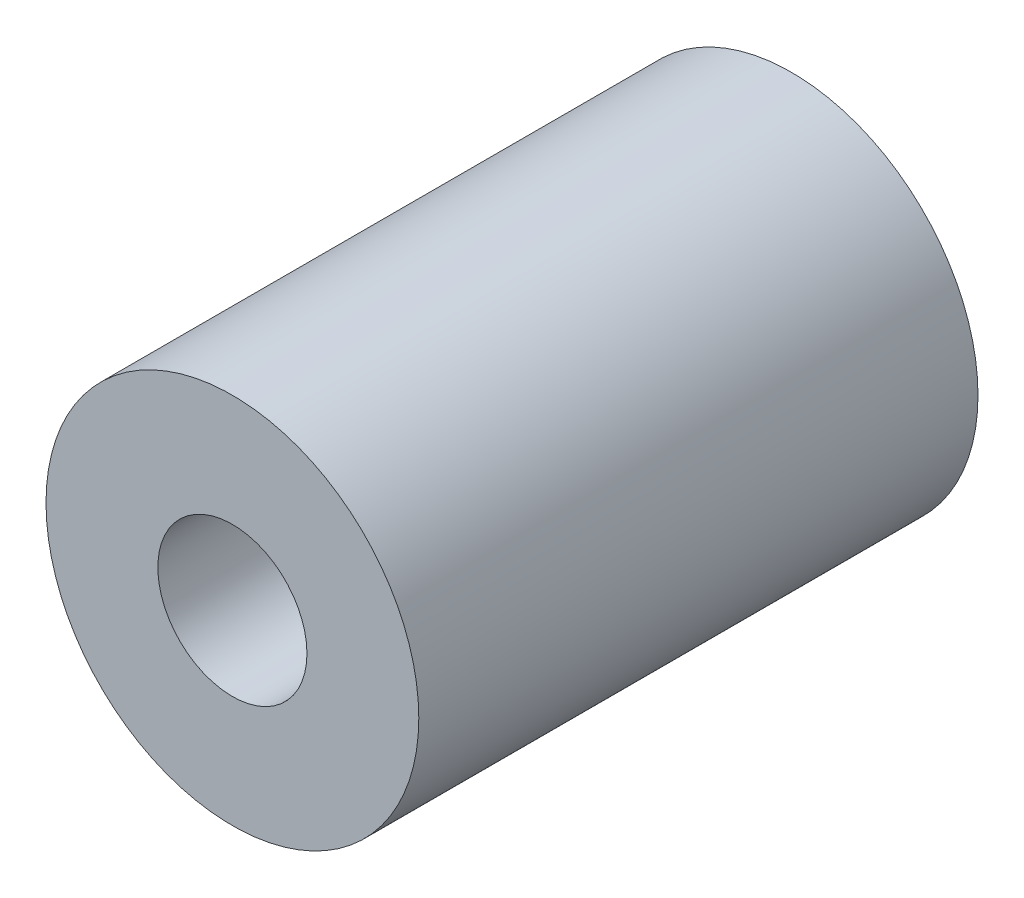
SolidWorks part; units mm, degrees
material "Alloy Steel"
ref_plane "Front Plane" through (0, 0, 0) normal (0, 0, 1) x (1, 0, 0)
ref_plane "Top Plane" through (0, 0, 0) normal (0, 1, 0) x (1, 0, 0)
ref_plane "Right Plane" through (0, 0, 0) normal (1, 0, 0) x (0, 0, -1)
sketch "Sketch1" plane through (0, 0, 0) normal (0, 0, 1) x (1, 0, 0)
  circle A0 centre (0, 0) radius 10
  dimension "D1" = 20
extrude "Boss-Extrude1" add sketch "Sketch1" along normal blind 30 contours A0
sketch "Sketch2" plane through (0, 0, 30) normal (0, 0, 1) x (1, 0, 0)
  circle A0 centre (0, 0) radius 4
  dimension "D1" = 8
extrude "Cut-Extrude1" cut sketch "Sketch2" against normal blind 30
